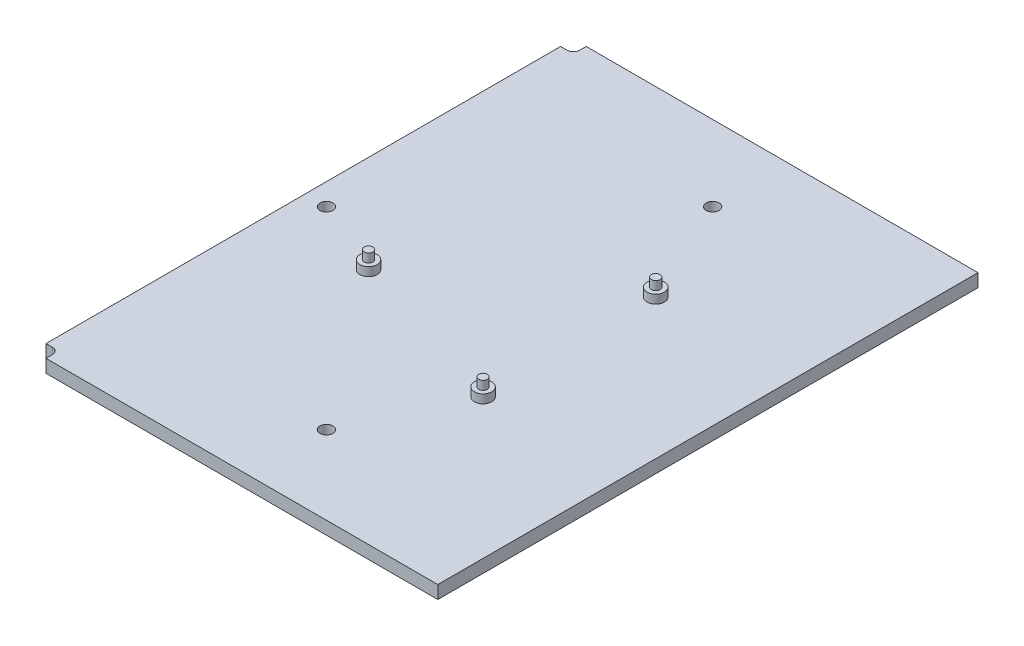
SolidWorks part; units mm, degrees
ref_plane "Front Plane" through (0, 0, 0) normal (0, 0, 1) x (1, 0, 0)
ref_plane "Top Plane" through (0, 0, 0) normal (0, 1, 0) x (1, 0, 0)
ref_plane "Right Plane" through (0, 0, 0) normal (1, 0, 0) x (0, 0, -1)
sketch "Sketch1" plane through (0, 0, 0) normal (0, 1, 0) x (1, 0, 0)
  line L1 (-46.625, -62.25) -> (46.625, -62.25)
  line L2 (-46.625, -62.25) -> (-46.625, 62.25)
  line L3 (-46.625, 62.25) -> (46.625, 62.25)
  line L4 (46.625, -62.25) -> (46.625, 62.25)
  line L5 (-46.625, -62.25) -> (46.625, 62.25) construction
  line L6 (-46.625, 62.25) -> (46.625, -62.25) construction
  point P0 (0, 0)
  dimension "D1" = 93.25
  dimension "D2" = 124.5
extrude "Boss-Extrude1" add sketch "Sketch1" along normal blind 3
sketch "Sketch2" plane through (0, 3, 0) normal (0, 1, 0) x (1, 0, 0)
  line L0 (-46.625, 62.25) -> (-46.625, -62.25) construction
  line L1 (46.625, 62.25) -> (-46.625, 62.25) construction
  line L2 (-46.625, -62.25) -> (46.625, -62.25) construction
  circle A0 centre (-45.125, 60.75) radius 1.45
  circle A1 centre (-45.125, -60.75) radius 1.45
  dimension "D1" = 2.9
  dimension "D4" = 2.9
  dimension "D2" = 1.5
  dimension "D3" = 1.5
  dimension "D5" = 1.5
  dimension "D6" = 1.5
extrude "Cut-Extrude1" cut sketch "Sketch2" against normal through all
sketch "Sketch6" plane through (0, 3, 0) normal (0, 1, 0) x (1, 0, 0)
  circle A0 centre (-24.225, -7.3673) radius 1
  circle A1 centre (14.375, 20.2327) radius 1
  circle A2 centre (14.375, -19.5673) radius 1
  circle A3 centre (-24.225, -7.3673) radius 2
  circle A4 centre (14.375, 20.2327) radius 2
  circle A5 centre (14.375, -19.5673) radius 2
  dimension "D1" = 2
  dimension "D2" = 4
extrude "Boss-Extrude4" add sketch "Sketch6" along normal blind 2
sketch "Sketch7" plane through (0, 3, 0) normal (0, 1, 0) x (1, 0, 0)
  circle A0 centre (-24.225, -7.3673) radius 1
  circle A1 centre (14.375, 20.2327) radius 1
  circle A2 centre (14.375, -19.5673) radius 1
  dimension "D1" = 2
extrude "Boss-Extrude5" add sketch "Sketch7" along normal blind 4
sketch "Sketch8" plane through (0, 3, 0) normal (0, 1, 0) x (1, 0, 0)
  circle A0 centre (2.875, 44.8327) radius 1.5
  circle A1 centre (-41.625, 0.3327) radius 1.5
  circle A2 centre (2.875, -44.1673) radius 1.5
  dimension "D1" = 3
extrude "Cut-Extrude2" cut sketch "Sketch8" against normal blind 3
sketch "Sketch9" plane through (0, 3, 0) normal (0, 1, 0) x (1, 0, 0)
  line L0 (-45.125, 59.3) -> (-46.625, 59.3)
  line L2 (-46.625, 62.25) -> (-46.625, -62.25) construction
  line L3 (-46.625, 59.3) -> (-46.625, 62.25)
  line L5 (-46.625, 62.25) -> (-43.675, 62.25)
  line L6 (46.625, 62.25) -> (-46.625, 62.25) construction
  line L7 (-43.675, 62.25) -> (-43.675, 60.75)
  circle A1 centre (-45.125, 60.75) radius 1.45 construction
  arc A2 (-45.125, 59.3) -> (-43.675, 60.75) centre (-45.125, 60.75) ccw
extrude "Cut-Extrude3" cut sketch "Sketch9" against normal blind 3
sketch "Sketch10" plane through (0, 3, 0) normal (0, 1, 0) x (1, 0, 0)
  line L0 (-45.125, -59.3) -> (-46.625, -59.3)
  line L1 (-46.625, 59.3) -> (-46.625, -62.25) construction
  line L2 (-46.625, -59.3) -> (-46.625, -62.25)
  line L3 (-46.625, -62.25) -> (-43.675, -62.25)
  line L4 (-46.625, -62.25) -> (46.625, -62.25) construction
  line L5 (-43.675, -62.25) -> (-43.675, -60.75)
  circle A0 centre (-45.125, -60.75) radius 1.45 construction
  arc A1 (-43.675, -60.75) -> (-45.125, -59.3) centre (-45.125, -60.75) ccw
extrude "Cut-Extrude4" cut sketch "Sketch10" against normal blind 3
